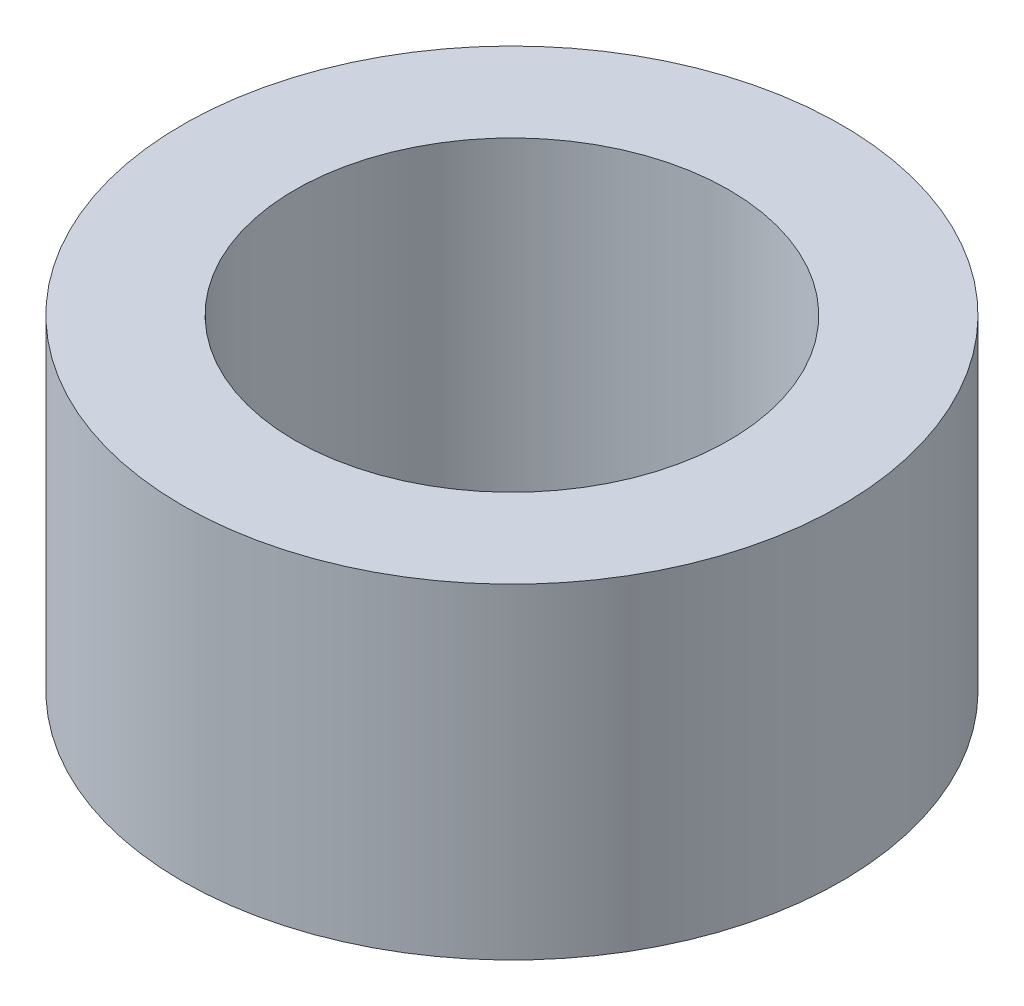
SolidWorks part; units mm, degrees
ref_plane "Front Plane" through (0, 0, 0) normal (0, 0, 1) x (1, 0, 0)
ref_plane "Top Plane" through (0, 0, 0) normal (0, 1, 0) x (1, 0, 0)
ref_plane "Right Plane" through (0, 0, 0) normal (1, 0, 0) x (0, 0, -1)
sketch "Sketch1" plane through (0, 0, 0) normal (0, 1, 0) x (1, 0, 0)
  circle A0 centre (0, 0) radius 6.075
  circle A1 centre (0, 0) radius 4
  dimension "D1" = 8
  dimension "D2" = 12.15
extrude "Boss-Extrude1" add sketch "Sketch1" along normal blind 6
